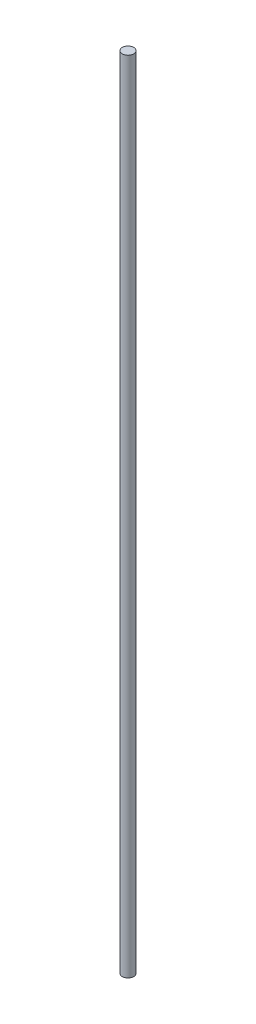
SolidWorks part; units mm, degrees
ref_plane "Front Plane" through (0, 0, 0) normal (0, 0, 1) x (1, 0, 0)
ref_plane "Top Plane" through (0, 0, 0) normal (0, 1, 0) x (1, 0, 0)
ref_plane "Right Plane" through (0, 0, 0) normal (1, 0, 0) x (0, 0, -1)
sketch "Sketch1" plane through (0, 0, 0) normal (0, 1, 0) x (1, 0, 0)
  circle A0 centre (0, 0) radius 3.9688
extrude "Boss-Extrude1" add sketch "Sketch1" along normal blind 558.8
